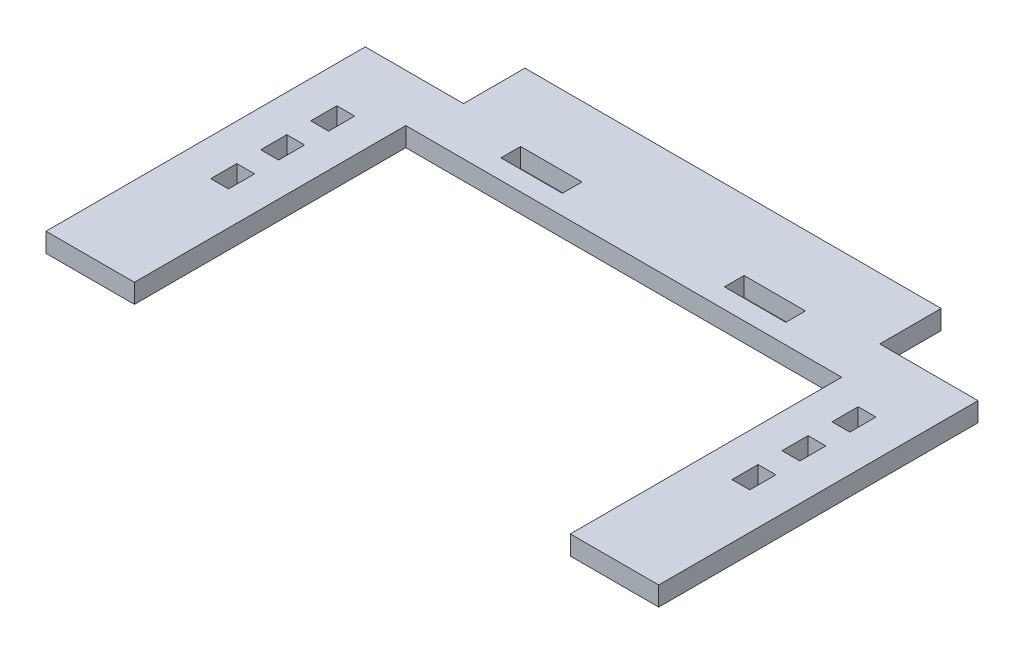
SolidWorks part; units mm, degrees
ref_plane "Front Plane" through (0, 0, 0) normal (0, 0, 1) x (1, 0, 0)
ref_plane "Top Plane" through (0, 0, 0) normal (0, 1, 0) x (1, 0, 0)
ref_plane "Right Plane" through (0, 0, 0) normal (1, 0, 0) x (0, 0, -1)
sketch "Sketch1" plane through (0, 0, 0) normal (0, 1, 0) x (1, 0, 0)
  line L0 (-68.5345, 15.1174) -> (-52.5345, 15.1174)
  line L2 (-68.5345, 15.1174) -> (-68.5345, -36.8826)
  line L3 (-68.5345, -36.8826) -> (31.2655, -36.8826)
  line L4 (31.2655, 15.1174) -> (31.2655, -36.8826)
  line L5 (-62.5345, 4.4924) -> (-59.6345, 4.4924)
  line L6 (-62.5345, 4.4924) -> (-62.5345, 0.2424)
  line L7 (-62.5345, 0.2424) -> (-59.6345, 0.2424)
  line L8 (-59.6345, 4.4924) -> (-59.6345, 0.2424)
  line L9 (-62.5345, -3.6576) -> (-59.6345, -3.6576)
  line L10 (-62.5345, -3.6576) -> (-62.5345, -7.9076)
  line L11 (-62.5345, -7.9076) -> (-59.6345, -7.9076)
  line L12 (-59.6345, -3.6576) -> (-59.6345, -7.9076)
  line L13 (-62.5345, -11.8076) -> (-59.6345, -11.8076)
  line L14 (-62.5345, -11.8076) -> (-62.5345, -16.0576)
  line L15 (-62.5345, -16.0576) -> (-59.6345, -16.0576)
  line L16 (-59.6345, -11.8076) -> (-59.6345, -16.0576)
  line L17 (25.2655, 4.4924) -> (22.3655, 4.4924)
  line L18 (25.2655, 4.4924) -> (25.2655, 0.2424)
  line L19 (25.2655, 0.2424) -> (22.3655, 0.2424)
  line L20 (22.3655, 4.4924) -> (22.3655, 0.2424)
  line L21 (22.3655, -3.6576) -> (25.2655, -3.6576)
  line L22 (22.3655, -3.6576) -> (22.3655, -7.9076)
  line L23 (22.3655, -7.9076) -> (25.2655, -7.9076)
  line L24 (25.2655, -3.6576) -> (25.2655, -7.9076)
  line L25 (22.3655, -11.8076) -> (25.2655, -11.8076)
  line L26 (22.3655, -11.8076) -> (22.3655, -16.0576)
  line L27 (22.3655, -16.0576) -> (25.2655, -16.0576)
  line L28 (25.2655, -11.8076) -> (25.2655, -16.0576)
  line L33 (-52.5345, 25.1174) -> (15.2655, 25.1174)
  line L34 (15.2655, 15.1174) -> (31.2655, 15.1174)
  line L35 (-52.5345, 15.1174) -> (-52.5345, 25.1174)
  line L36 (15.2655, 25.1174) -> (15.2655, 15.1174)
  line L38 (-41.8345, 13.7174) -> (-31.8345, 13.7174)
  line L39 (-41.8345, 13.7174) -> (-41.8345, 10.5174)
  line L40 (-41.8345, 10.5174) -> (-31.8345, 10.5174)
  line L41 (-31.8345, 13.7174) -> (-31.8345, 10.5174)
  line L42 (-5.4345, 13.7174) -> (4.5655, 13.7174)
  line L43 (-5.4345, 13.7174) -> (-5.4345, 10.5174)
  line L44 (-5.4345, 10.5174) -> (4.5655, 10.5174)
  line L45 (4.5655, 13.7174) -> (4.5655, 10.5174)
  point P8 (-61.0845, 0.2424)
  point P29 (25.2655, -5.7826)
  point P30 (23.8155, -7.9076)
  point P31 (23.8155, -11.8076)
  point P36 (-60.5345, 15.1174)
  point P37 (23.8155, 4.4924)
  dimension "D1" = 99.8
  dimension "D2" = 52
  dimension "D3" = 6
  dimension "D4" = 10.625
  dimension "D5" = 4.25
  dimension "D6" = 2.9
  dimension "D7" = 4.25
  dimension "D8" = 3.9
  dimension "D9" = 3.9
  dimension "D10" = 4.25
  dimension "D11" = 10.625
  dimension "D12" = 6
  dimension "D13" = 2.9
  dimension "D14" = 4.25
  dimension "D15" = 2.9
  dimension "D16" = 2.9
  dimension "D17" = 4.25
  dimension "D18" = 3.9
  dimension "D19" = 10
  dimension "D20" = 26.7
  dimension "D21" = 3.2
  dimension "D22" = 11.4
  dimension "D23" = 3.2
  dimension "D24" = 10
  dimension "D25" = 11.4
  dimension "D26" = 10
  dimension "D27" = 26.7
extrude "Boss-Extrude1" add sketch "Sketch1" along normal blind 3.125
sketch "Sketch3" plane through (0, 3.125, 0) normal (0, 1, 0) x (1, 0, 0)
  line L0 (-68.5345, -36.8826) -> (31.2655, -36.8826) construction
  line L1 (-54.1345, -36.8826) -> (16.8655, -36.8826)
  line L2 (-54.1345, -36.8826) -> (-54.1345, 7.3174)
  line L3 (-54.1345, 7.3174) -> (16.8655, 7.3174)
  line L4 (16.8655, -36.8826) -> (16.8655, 7.3174)
  line L5 (-68.5345, 15.1174) -> (-68.5345, -36.8826) construction
  line L10 (31.2655, -36.8826) -> (31.2655, 15.1174) construction
  line L11 (15.2655, 25.1174) -> (-52.5345, 25.1174) construction
  dimension "D1" = 14.4
  dimension "D2" = 14.4
  dimension "D3" = 17.8
extrude "Cut-Extrude1" cut sketch "Sketch3" against normal blind 3.125
